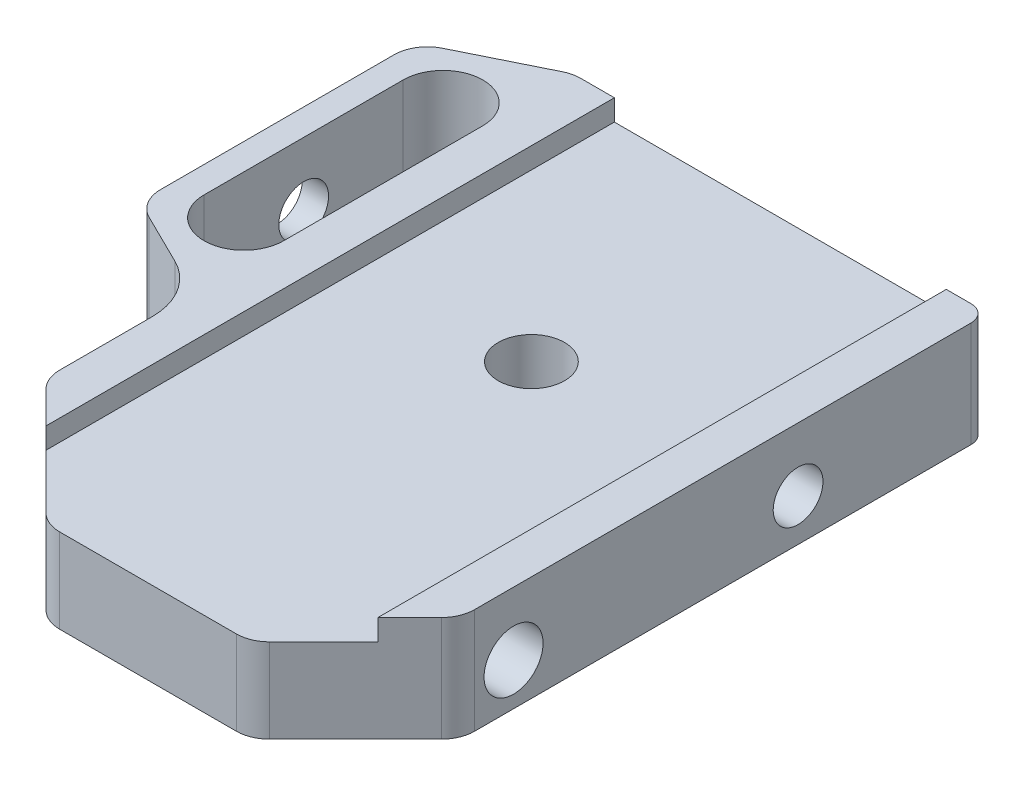
SolidWorks part; units mm, degrees
ref_plane "Front" through (0, 0, 0) normal (0, 0, 1) x (1, 0, 0)
ref_plane "Top" through (0, 0, 0) normal (0, 1, 0) x (1, 0, 0)
ref_plane "Right" through (0, 0, 0) normal (1, 0, 0) x (0, 0, -1)
ref_plane "Plane1" through (0, 6.35, 0) normal (0, 1, 0) x (1, 0, 0)
sketch "Sketch1" plane through (0, 6.35, 0) normal (0, 1, 0) x (1, 0, 0)
  line L0 (-6.3812, -3.1467) -> (-6.3812, -31.75)
  line L1 (-6.3812, -31.75) -> (0, -31.75)
  line L2 (0, -31.75) -> (2.5, -34.25)
  line L3 (2.5, -34.25) -> (2.5, 0)
  line L4 (2.5, 0) -> (0, 0)
  line L5 (0, 0) -> (-6.3812, -3.1467)
extrude "Boss-Extrude1" add sketch "Sketch1" against normal blind 1.27
sketch "Sketch2" plane through (0, 0, 31.75) normal (0, 0, 1) x (1, 0, 0)
  line L0 (-6.3812, 6.35) -> (-6.3812, 5.08)
  line L1 (-6.3812, 5.08) -> (0, 5.08)
  line L2 (0, 5.08) -> (0, 6.35)
  line L3 (0, 6.35) -> (-6.3812, 6.35)
extrude "Cut-Extrude1" cut sketch "Sketch2" against normal blind 8.89
sketch "Sketch3" plane through (0, 5.08, 0) normal (0, -1, 0) x (1, 0, 0)
  line L0 (25, 0) -> (0, 0)
  line L1 (0, 0) -> (-6.3813, 3.1467)
  line L2 (-6.3813, 3.1467) -> (-6.3812, 22.86)
  line L3 (-6.3812, 22.86) -> (0, 22.86)
  line L4 (0, 22.86) -> (0, 31.75)
  line L5 (0, 31.75) -> (6.35, 38.1)
  line L6 (6.35, 38.1) -> (18.65, 38.1)
  line L7 (18.65, 38.1) -> (25, 31.75)
  line L8 (25, 31.75) -> (25, 0)
extrude "Boss-Extrude2" add sketch "Sketch3" along normal blind 5.08
sketch "Sketch4" plane through (0, 5.08, 0) normal (0, 1, 0) x (-1, 0, 0)
  line L0 (-25, 31.75) -> (-22.5, 34.25)
  line L1 (-22.5, 34.25) -> (-22.5, 0)
  line L2 (-22.5, 0) -> (-25, 0)
  line L3 (-25, 0) -> (-25, 31.75)
extrude "Boss-Extrude3" add sketch "Sketch4" along normal blind 1.27
sketch "Sketch5" plane through (0, 0, 0) normal (0, -1, 0) x (1, 0, 0)
  line L0 (-4.7937, 17.43) -> (-4.7937, 5.43)
  line L1 (0, 5.43) -> (0, 17.43)
  arc A0 (0, 17.43) -> (-4.7937, 17.43) centre (-2.3969, 17.43) ccw
  arc A1 (-4.7937, 5.43) -> (0, 5.43) centre (-2.3969, 5.43) ccw
extrude "Cut-Extrude2" cut sketch "Sketch5" against normal through all
draft "Draft1" type of draft neutral plane draft angle 26.249 faces to draft 1 face at (-3.1906, 3.175, 22.86) neutral plane through (0, 5.08, 22.86) neutral plane normal (-1, 0, 0) parameters "D1"=26.249
hole_wizard "#6 Clearance Hole1" positions "Sketch7" profile "Sketch6" hole size "#6" standard "ANSI Inch"
sketch "Sketch7" plane through (0, 5.08, 0) normal (0, 1, 0) x (1, 0, 0)
  point P0 (12.5, -15)
sketch "Sketch6" plane through (12.5, 5.08, 15) normal (1, 0, 0) x (0, 0, 1)
  line L0 (0, 0) -> (0, 5.08)
  line L1 (0, 5.08) -> (2, 5.08)
  line L2 (2, 5.08) -> (2, 0)
  line L5 (2, 0) -> (0, 0)
  line L11 (0, -6.35) -> (0, 107.95) construction
  dimension "Thru Hole Dia." = 4
  dimension "Thru Hole Depth" = 5.08
hole_wizard "#3 Clearance Hole1" positions "Sketch9" profile "Sketch8" hole size "#3" standard "ANSI Inch"
sketch "Sketch9" plane through (-6.3812, 0, 0) normal (-1, 0, 0) x (0, 0, 1)
  point P0 (11.43, 2.54)
sketch "Sketch8" plane through (-6.3812, 2.54, 11.43) normal (0, 1, 0) x (0, 0, 1)
  line L0 (0, 0) -> (0, 56.3812)
  line L1 (0, 56.3812) -> (1.5, 56.3813)
  line L2 (1.5, 56.3813) -> (1.5, 0)
  line L5 (1.5, 0) -> (0, 0)
  line L10 (0, 56.3812) -> (-1.5, 56.3813) construction
  line L11 (0, -6.35) -> (0, 107.95) construction
  dimension "Hole Dia." = 3
  dimension "Hole Depth" = 56.3813
  dimension "Drill Angle" = 180
hole_wizard "#5 Clearance Hole1" positions "Sketch11" profile "Sketch10" hole size "#5" standard "ANSI Inch"
sketch "Sketch11" plane through (0, 0, 0) normal (-1, 0, 0) x (0, 0, 1)
  point P0 (28.575, 2.54)
sketch "Sketch10" plane through (0, 2.54, 28.575) normal (0, 1, 0) x (0, 0, 1)
  line L0 (0, 0) -> (0, 25)
  line L1 (0, 25) -> (1.778, 25)
  line L2 (1.778, 25) -> (1.778, 0)
  line L5 (1.778, 0) -> (0, 0)
  line L11 (0, -6.35) -> (0, 107.95) construction
  dimension "Thru Hole Dia." = 3.556
  dimension "Thru Hole Depth" = 25
fillet "Fillet1" radius 1 1 edges at (25, 3.175, 0)
fillet "Fillet2" radius 2 7 edges at (-6.3812, 3.175, 3.1467) (0, 3.175, 31.75) (6.35, 2.54, 38.1) (-6.3812, 3.175, 19.7133) (18.65, 2.54, 38.1) (25, 3.175, 31.75) (0, 3.175, 0)
fillet "Fillet3" radius 4 1 edges at (0, 3.175, 22.86)
